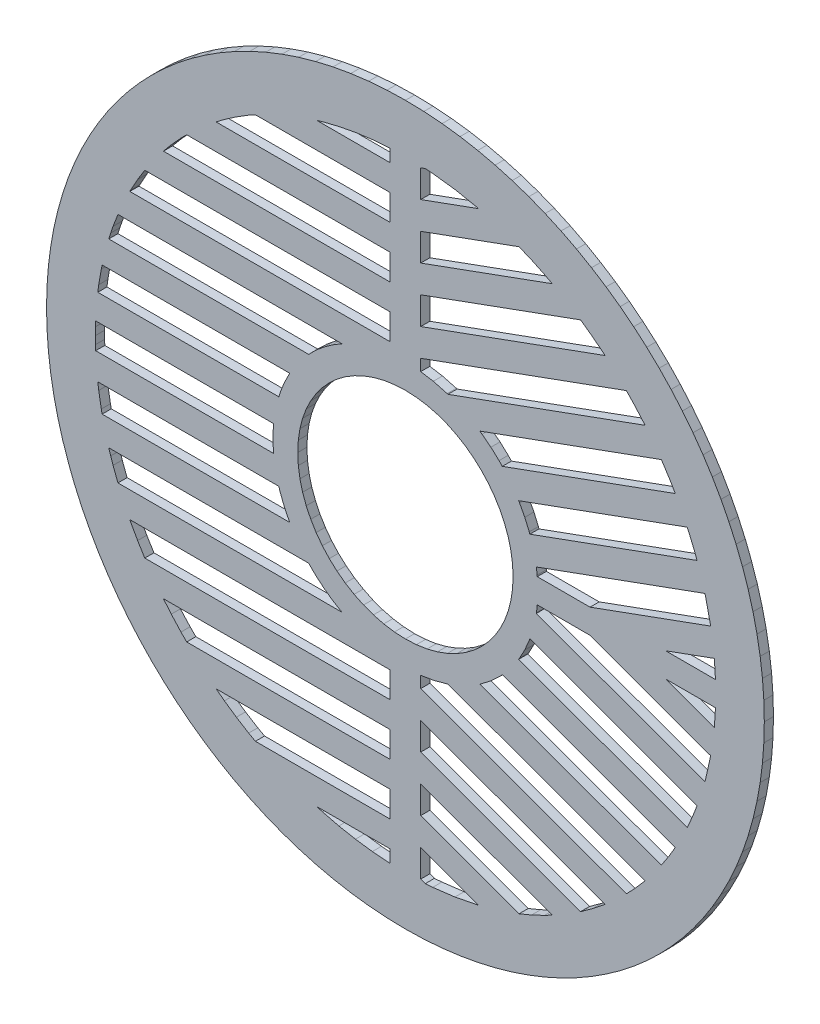
SolidWorks part; units mm, degrees
ref_plane "Front Plane" through (0, 0, 0) normal (0, 0, 1) x (1, 0, 0)
ref_plane "Top Plane" through (0, 0, 0) normal (0, 1, 0) x (1, 0, 0)
ref_plane "Right Plane" through (0, 0, 0) normal (1, 0, 0) x (0, 0, -1)
sketch "Model" plane through (0, 0, 0) normal (0, 0, 1) x (1, 0, 0)
  line L0 (88.7253, -26.6817) -> (90.6925, -27.2511)
  line L1 (90.6925, -27.2511) -> (96.018, -28.5686)
  line L2 (96.018, -28.5686) -> (101.4499, -29.6019)
  line L3 (101.4499, -29.6019) -> (106.9798, -30.3428)
  line L4 (106.9798, -30.3428) -> (112.5994, -30.7829)
  line L5 (112.5994, -30.7829) -> (113.8278, -30.8296)
  line L6 (113.8278, -30.8296) -> (113.8278, -26.6817)
  line L7 (113.8278, -26.6817) -> (88.7253, -26.6817)
  line L8 (121.8278, -20.8713) -> (121.8278, -29.8813)
  line L9 (121.8278, -29.8813) -> (124.32, -30.7884)
  line L10 (124.32, -30.7884) -> (126.7677, -30.6053)
  line L11 (126.7677, -30.6053) -> (134.0501, -29.7079)
  line L12 (134.0501, -29.7079) -> (141.1631, -28.3079)
  line L13 (141.1631, -28.3079) -> (141.8166, -28.1466)
  line L14 (141.8166, -28.1466) -> (121.8278, -20.8713)
  line L15 (55.7826, -9.7483) -> (58.5159, -11.8148)
  line L16 (58.5159, -11.8148) -> (62.4239, -14.4936)
  line L17 (62.4239, -14.4936) -> (66.4601, -16.992)
  line L18 (66.4601, -16.992) -> (68.6597, -18.215)
  line L19 (68.6597, -18.215) -> (113.8278, -18.215)
  line L20 (113.8278, -18.215) -> (113.8278, -9.7483)
  line L21 (113.8278, -9.7483) -> (55.7826, -9.7483)
  line L22 (121.8278, -2.8512) -> (121.8278, -11.8612)
  line L23 (121.8278, -11.8612) -> (155.0747, -23.9621)
  line L24 (155.0747, -23.9621) -> (159.1619, -22.2578)
  line L25 (159.1619, -22.2578) -> (163.4116, -20.2484)
  line L26 (163.4116, -20.2484) -> (165.9394, -18.9065)
  line L27 (165.9394, -18.9065) -> (121.8278, -2.8512)
  line L28 (38.529, 7.185) -> (41.103, 4.0802)
  line L29 (41.103, 4.0802) -> (44.2827, 0.587)
  line L30 (44.2827, 0.587) -> (46.1485, -1.2817)
  line L31 (46.1485, -1.2817) -> (113.8278, -1.2817)
  line L32 (113.8278, -1.2817) -> (113.8278, 7.185)
  line L33 (113.8278, 7.185) -> (38.529, 7.185)
  line L34 (121.8278, 15.1689) -> (121.8278, 6.1588)
  line L35 (121.8278, 6.1588) -> (175.2272, -13.2769)
  line L36 (175.2272, -13.2769) -> (175.4731, -13.1157)
  line L37 (175.4731, -13.1157) -> (179.2461, -10.3883)
  line L38 (179.2461, -10.3883) -> (182.8862, -7.495)
  line L39 (182.8862, -7.495) -> (183.2425, -7.1843)
  line L40 (183.2425, -7.1843) -> (121.8278, 15.1689)
  line L41 (27.5169, 24.1183) -> (27.767, 23.6121)
  line L42 (27.767, 23.6121) -> (30.0733, 19.4496)
  line L43 (30.0733, 19.4496) -> (32.4163, 15.6517)
  line L44 (32.4163, 15.6517) -> (113.8278, 15.6517)
  line L45 (113.8278, 15.6517) -> (113.8278, 24.1183)
  line L46 (113.8278, 24.1183) -> (27.5169, 24.1183)
  line L47 (131.7462, 29.579) -> (131.4924, 29.4887)
  line L48 (131.4924, 29.4887) -> (126.9693, 28.258)
  line L49 (126.9693, 28.258) -> (122.2643, 27.5174)
  line L50 (122.2643, 27.5174) -> (121.8278, 27.4842)
  line L51 (121.8278, 27.4842) -> (121.8278, 24.1789)
  line L52 (121.8278, 24.1789) -> (190.2361, -0.7197)
  line L53 (190.2361, -0.7197) -> (192.9542, 2.1249)
  line L54 (192.9542, 2.1249) -> (196.0078, 5.6266)
  line L55 (196.0078, 5.6266) -> (196.3549, 6.0633)
  line L56 (196.3549, 6.0633) -> (131.7462, 29.579)
  line L57 (20.6207, 41.0517) -> (21.2461, 39.06)
  line L58 (21.2461, 39.06) -> (22.0242, 36.7752)
  line L59 (22.0242, 36.7752) -> (23.6208, 32.585)
  line L60 (23.6208, 32.585) -> (97.0674, 32.585)
  line L61 (97.0674, 32.585) -> (96.343, 32.9771)
  line L62 (96.343, 32.9771) -> (93.8383, 34.5222)
  line L63 (93.8383, 34.5222) -> (91.4501, 36.2285)
  line L64 (91.4501, 36.2285) -> (89.1859, 38.0885)
  line L65 (89.1859, 38.0885) -> (87.0533, 40.0946)
  line L66 (87.0533, 40.0946) -> (86.1436, 41.0517)
  line L67 (86.1436, 41.0517) -> (20.6207, 41.0517)
  line L68 (149.5731, 41.1106) -> (148.5103, 40.0025)
  line L69 (148.5103, 40.0025) -> (145.8287, 37.5359)
  line L70 (145.8287, 37.5359) -> (142.9467, 35.2989)
  line L71 (142.9467, 35.2989) -> (142.1932, 34.7866)
  line L72 (142.1932, 34.7866) -> (201.689, 13.1319)
  line L73 (201.689, 13.1319) -> (204.1847, 16.94)
  line L74 (204.1847, 16.94) -> (206.2746, 20.4729)
  line L75 (206.2746, 20.4729) -> (149.5731, 41.1106)
  line L76 (158.6054, 55.8432) -> (158.401, 55.2685)
  line L77 (158.401, 55.2685) -> (156.9405, 51.8729)
  line L78 (156.9405, 51.8729) -> (155.2067, 48.6339)
  line L79 (155.2067, 48.6339) -> (154.9215, 48.174)
  line L80 (154.9215, 48.174) -> (210.1637, 28.0674)
  line L81 (210.1637, 28.0674) -> (210.7706, 29.3509)
  line L82 (210.7706, 29.3509) -> (212.5867, 33.7061)
  line L83 (212.5867, 33.7061) -> (213.385, 35.905)
  line L84 (213.385, 35.905) -> (158.6054, 55.8432)
  line L85 (17.0156, 57.985) -> (17.3272, 55.6856)
  line L86 (17.3272, 55.6856) -> (18.1668, 50.8298)
  line L87 (18.1668, 50.8298) -> (18.4432, 49.5183)
  line L88 (18.4432, 49.5183) -> (79.9425, 49.5183)
  line L89 (79.9425, 49.5183) -> (79.064, 51.1652)
  line L90 (79.064, 51.1652) -> (77.8204, 53.8559)
  line L91 (77.8204, 53.8559) -> (76.7588, 56.6421)
  line L92 (76.7588, 56.6421) -> (76.3343, 57.985)
  line L93 (76.3343, 57.985) -> (17.0156, 57.985)
  line L94 (203.0823, 66.685) -> (219.0323, 60.8797)
  line L95 (219.0323, 60.8797) -> (219.118, 61.7451)
  line L96 (219.118, 61.7451) -> (219.4279, 66.685)
  line L97 (219.4279, 66.685) -> (203.0823, 66.685)
  line L98 (161.0286, 66.685) -> (160.9954, 66.2485)
  line L99 (160.9954, 66.2485) -> (160.7598, 64.3465)
  line L100 (160.7598, 64.3465) -> (160.7157, 64.0851)
  line L101 (160.7157, 64.0851) -> (215.9618, 43.9772)
  line L102 (215.9618, 43.9772) -> (216.2455, 45.0195)
  line L103 (216.2455, 45.0195) -> (217.809, 52.0719)
  line L104 (217.809, 52.0719) -> (217.8484, 52.3006)
  line L105 (217.8484, 52.3006) -> (178.3275, 66.685)
  line L106 (178.3275, 66.685) -> (161.0286, 66.685)
  line L107 (16.3211, 74.9183) -> (16.2588, 73.2256)
  line L108 (16.2588, 73.2256) -> (16.2277, 70.685)
  line L109 (16.2277, 70.685) -> (16.2588, 68.1444)
  line L110 (16.2588, 68.1444) -> (16.3211, 66.4517)
  line L111 (16.3211, 66.4517) -> (74.6416, 66.4517)
  line L112 (74.6416, 66.4517) -> (74.6332, 66.5222)
  line L113 (74.6332, 66.5222) -> (74.4858, 68.5908)
  line L114 (74.4858, 68.5908) -> (74.4361, 70.685)
  line L115 (74.4361, 70.685) -> (74.4858, 72.7792)
  line L116 (74.4858, 72.7792) -> (74.6332, 74.8478)
  line L117 (74.6332, 74.8478) -> (74.6416, 74.9183)
  line L118 (74.6416, 74.9183) -> (16.3211, 74.9183)
  line L119 (219.0323, 80.4903) -> (203.0823, 74.685)
  line L120 (203.0823, 74.685) -> (219.4279, 74.685)
  line L121 (219.4279, 74.685) -> (219.118, 79.6249)
  line L122 (219.118, 79.6249) -> (219.0323, 80.4903)
  line L123 (18.4432, 91.8517) -> (18.1668, 90.5402)
  line L124 (18.1668, 90.5402) -> (17.3272, 85.6844)
  line L125 (17.3272, 85.6844) -> (17.0156, 83.385)
  line L126 (17.0156, 83.385) -> (76.3343, 83.385)
  line L127 (76.3343, 83.385) -> (76.7588, 84.7279)
  line L128 (76.7588, 84.7279) -> (77.8204, 87.5141)
  line L129 (77.8204, 87.5141) -> (79.064, 90.2048)
  line L130 (79.064, 90.2048) -> (79.9425, 91.8517)
  line L131 (79.9425, 91.8517) -> (18.4432, 91.8517)
  line L132 (215.9618, 97.3928) -> (160.7157, 77.2849)
  line L133 (160.7157, 77.2849) -> (160.7598, 77.0235)
  line L134 (160.7598, 77.0235) -> (160.9954, 75.1216)
  line L135 (160.9954, 75.1216) -> (161.0286, 74.685)
  line L136 (161.0286, 74.685) -> (178.3275, 74.685)
  line L137 (178.3275, 74.685) -> (217.8484, 89.0694)
  line L138 (217.8484, 89.0694) -> (217.809, 89.2981)
  line L139 (217.809, 89.2981) -> (216.2455, 96.3505)
  line L140 (216.2455, 96.3505) -> (215.9618, 97.3928)
  line L141 (117.8278, 105.9628) -> (114.2208, 105.7807)
  line L142 (114.2208, 105.7807) -> (110.7181, 105.2461)
  line L143 (110.7181, 105.2461) -> (107.3372, 104.3768)
  line L144 (107.3372, 104.3768) -> (104.0961, 103.1905)
  line L145 (104.0961, 103.1905) -> (101.0123, 101.705)
  line L146 (101.0123, 101.705) -> (98.1036, 99.9379)
  line L147 (98.1036, 99.9379) -> (95.3878, 97.9071)
  line L148 (95.3878, 97.9071) -> (92.8826, 95.6302)
  line L149 (92.8826, 95.6302) -> (90.6057, 93.1249)
  line L150 (90.6057, 93.1249) -> (88.5749, 90.4091)
  line L151 (88.5749, 90.4091) -> (86.8078, 87.5005)
  line L152 (86.8078, 87.5005) -> (85.3223, 84.4167)
  line L153 (85.3223, 84.4167) -> (84.136, 81.1755)
  line L154 (84.136, 81.1755) -> (83.2667, 77.7947)
  line L155 (83.2667, 77.7947) -> (82.7321, 74.292)
  line L156 (82.7321, 74.292) -> (82.55, 70.685)
  line L157 (82.55, 70.685) -> (82.7321, 67.0781)
  line L158 (82.7321, 67.0781) -> (83.2667, 63.5753)
  line L159 (83.2667, 63.5753) -> (84.136, 60.1945)
  line L160 (84.136, 60.1945) -> (85.3223, 56.9533)
  line L161 (85.3223, 56.9533) -> (86.8078, 53.8695)
  line L162 (86.8078, 53.8695) -> (88.5749, 50.9609)
  line L163 (88.5749, 50.9609) -> (90.6057, 48.2451)
  line L164 (90.6057, 48.2451) -> (92.8826, 45.7399)
  line L165 (92.8826, 45.7399) -> (95.3878, 43.463)
  line L166 (95.3878, 43.463) -> (98.1036, 41.4321)
  line L167 (98.1036, 41.4321) -> (101.0123, 39.6651)
  line L168 (101.0123, 39.6651) -> (104.0961, 38.1795)
  line L169 (104.0961, 38.1795) -> (107.3372, 36.9932)
  line L170 (107.3372, 36.9932) -> (110.7181, 36.1239)
  line L171 (110.7181, 36.1239) -> (114.2208, 35.5894)
  line L172 (114.2208, 35.5894) -> (117.8278, 35.4072)
  line L173 (117.8278, 35.4072) -> (121.4347, 35.5894)
  line L174 (121.4347, 35.5894) -> (124.9375, 36.1239)
  line L175 (124.9375, 36.1239) -> (128.3183, 36.9932)
  line L176 (128.3183, 36.9932) -> (131.5595, 38.1795)
  line L177 (131.5595, 38.1795) -> (134.6433, 39.6651)
  line L178 (134.6433, 39.6651) -> (137.5519, 41.4321)
  line L179 (137.5519, 41.4321) -> (140.2677, 43.463)
  line L180 (140.2677, 43.463) -> (142.7729, 45.7399)
  line L181 (142.7729, 45.7399) -> (145.0498, 48.2451)
  line L182 (145.0498, 48.2451) -> (147.0807, 50.9609)
  line L183 (147.0807, 50.9609) -> (148.8477, 53.8695)
  line L184 (148.8477, 53.8695) -> (150.3333, 56.9533)
  line L185 (150.3333, 56.9533) -> (151.5195, 60.1945)
  line L186 (151.5195, 60.1945) -> (152.3888, 63.5753)
  line L187 (152.3888, 63.5753) -> (152.9234, 67.0781)
  line L188 (152.9234, 67.0781) -> (153.1056, 70.685)
  line L189 (153.1056, 70.685) -> (152.9234, 74.292)
  line L190 (152.9234, 74.292) -> (152.3888, 77.7947)
  line L191 (152.3888, 77.7947) -> (151.5195, 81.1755)
  line L192 (151.5195, 81.1755) -> (150.3333, 84.4167)
  line L193 (150.3333, 84.4167) -> (148.8477, 87.5005)
  line L194 (148.8477, 87.5005) -> (147.0807, 90.4091)
  line L195 (147.0807, 90.4091) -> (145.0498, 93.1249)
  line L196 (145.0498, 93.1249) -> (142.7729, 95.6302)
  line L197 (142.7729, 95.6302) -> (140.2677, 97.9071)
  line L198 (140.2677, 97.9071) -> (137.5519, 99.9379)
  line L199 (137.5519, 99.9379) -> (134.6433, 101.705)
  line L200 (134.6433, 101.705) -> (131.5595, 103.1905)
  line L201 (131.5595, 103.1905) -> (128.3183, 104.3768)
  line L202 (128.3183, 104.3768) -> (124.9375, 105.2461)
  line L203 (124.9375, 105.2461) -> (121.4347, 105.7807)
  line L204 (121.4347, 105.7807) -> (117.8278, 105.9628)
  line L205 (23.6208, 108.785) -> (22.0242, 104.5948)
  line L206 (22.0242, 104.5948) -> (21.2461, 102.31)
  line L207 (21.2461, 102.31) -> (20.6207, 100.3183)
  line L208 (20.6207, 100.3183) -> (86.1436, 100.3183)
  line L209 (86.1436, 100.3183) -> (87.0533, 101.2754)
  line L210 (87.0533, 101.2754) -> (89.1859, 103.2815)
  line L211 (89.1859, 103.2815) -> (91.4501, 105.1415)
  line L212 (91.4501, 105.1415) -> (93.8383, 106.8478)
  line L213 (93.8383, 106.8478) -> (96.343, 108.3929)
  line L214 (96.343, 108.3929) -> (97.0674, 108.785)
  line L215 (97.0674, 108.785) -> (23.6208, 108.785)
  line L216 (210.1637, 113.3026) -> (154.9215, 93.196)
  line L217 (154.9215, 93.196) -> (155.2067, 92.7361)
  line L218 (155.2067, 92.7361) -> (156.9405, 89.4971)
  line L219 (156.9405, 89.4971) -> (158.401, 86.1015)
  line L220 (158.401, 86.1015) -> (158.6054, 85.5268)
  line L221 (158.6054, 85.5268) -> (213.385, 105.465)
  line L222 (213.385, 105.465) -> (212.5867, 107.6639)
  line L223 (212.5867, 107.6639) -> (210.7706, 112.0191)
  line L224 (210.7706, 112.0191) -> (210.1637, 113.3026)
  line L225 (32.4163, 125.7183) -> (30.0733, 121.9204)
  line L226 (30.0733, 121.9204) -> (27.767, 117.7579)
  line L227 (27.767, 117.7579) -> (27.5169, 117.2517)
  line L228 (27.5169, 117.2517) -> (113.8278, 117.2517)
  line L229 (113.8278, 117.2517) -> (113.8278, 125.7183)
  line L230 (113.8278, 125.7183) -> (32.4163, 125.7183)
  line L231 (201.689, 128.2381) -> (142.1932, 106.5834)
  line L232 (142.1932, 106.5834) -> (142.9467, 106.0711)
  line L233 (142.9467, 106.0711) -> (145.8287, 103.8342)
  line L234 (145.8287, 103.8342) -> (148.5103, 101.3675)
  line L235 (148.5103, 101.3675) -> (149.5731, 100.2594)
  line L236 (149.5731, 100.2594) -> (206.2746, 120.8971)
  line L237 (206.2746, 120.8971) -> (204.1847, 124.43)
  line L238 (204.1847, 124.43) -> (201.689, 128.2381)
  line L239 (190.2361, 142.0897) -> (121.8278, 117.1911)
  line L240 (121.8278, 117.1911) -> (121.8278, 113.8858)
  line L241 (121.8278, 113.8858) -> (122.2643, 113.8526)
  line L242 (122.2643, 113.8526) -> (126.9693, 113.112)
  line L243 (126.9693, 113.112) -> (131.4924, 111.8813)
  line L244 (131.4924, 111.8813) -> (131.7462, 111.791)
  line L245 (131.7462, 111.791) -> (196.3549, 135.3067)
  line L246 (196.3549, 135.3067) -> (196.0078, 135.7434)
  line L247 (196.0078, 135.7434) -> (192.9542, 139.2451)
  line L248 (192.9542, 139.2451) -> (190.2361, 142.0897)
  line L249 (46.1485, 142.6517) -> (44.2827, 140.783)
  line L250 (44.2827, 140.783) -> (41.103, 137.2898)
  line L251 (41.103, 137.2898) -> (38.529, 134.185)
  line L252 (38.529, 134.185) -> (113.8278, 134.185)
  line L253 (113.8278, 134.185) -> (113.8278, 142.6517)
  line L254 (113.8278, 142.6517) -> (46.1485, 142.6517)
  line L255 (175.2272, 154.647) -> (121.8278, 135.2112)
  line L256 (121.8278, 135.2112) -> (121.8278, 126.2011)
  line L257 (121.8278, 126.2011) -> (183.2425, 148.5543)
  line L258 (183.2425, 148.5543) -> (182.8862, 148.865)
  line L259 (182.8862, 148.865) -> (179.2461, 151.7583)
  line L260 (179.2461, 151.7583) -> (175.4731, 154.4858)
  line L261 (175.4731, 154.4858) -> (175.2272, 154.647)
  line L262 (68.6597, 159.585) -> (66.4601, 158.362)
  line L263 (66.4601, 158.362) -> (62.4239, 155.8636)
  line L264 (62.4239, 155.8636) -> (58.5159, 153.1848)
  line L265 (58.5159, 153.1848) -> (55.7826, 151.1183)
  line L266 (55.7826, 151.1183) -> (113.8278, 151.1183)
  line L267 (113.8278, 151.1183) -> (113.8278, 159.585)
  line L268 (113.8278, 159.585) -> (68.6597, 159.585)
  line L269 (155.0747, 165.3321) -> (121.8278, 153.2312)
  line L270 (121.8278, 153.2312) -> (121.8278, 144.2212)
  line L271 (121.8278, 144.2212) -> (165.9394, 160.2765)
  line L272 (165.9394, 160.2765) -> (163.4116, 161.6184)
  line L273 (163.4116, 161.6184) -> (159.1619, 163.6278)
  line L274 (159.1619, 163.6278) -> (155.0747, 165.3321)
  line L275 (124.32, 172.1584) -> (121.8278, 171.2513)
  line L276 (121.8278, 171.2513) -> (121.8278, 162.2413)
  line L277 (121.8278, 162.2413) -> (141.8166, 169.5166)
  line L278 (141.8166, 169.5166) -> (141.1631, 169.6779)
  line L279 (141.1631, 169.6779) -> (134.0501, 171.0779)
  line L280 (134.0501, 171.0779) -> (126.7677, 171.9753)
  line L281 (126.7677, 171.9753) -> (124.32, 172.1584)
  line L282 (113.8278, 172.1996) -> (112.5994, 172.1529)
  line L283 (112.5994, 172.1529) -> (106.9798, 171.7128)
  line L284 (106.9798, 171.7128) -> (101.4499, 170.9719)
  line L285 (101.4499, 170.9719) -> (96.018, 169.9386)
  line L286 (96.018, 169.9386) -> (90.6925, 168.6211)
  line L287 (90.6925, 168.6211) -> (88.7253, 168.0517)
  line L288 (88.7253, 168.0517) -> (113.8278, 168.0517)
  line L289 (113.8278, 168.0517) -> (113.8278, 172.1996)
  line L290 (117.8278, 188.2851) -> (123.8795, 188.1321)
  line L291 (123.8795, 188.1321) -> (129.8517, 187.6779)
  line L292 (129.8517, 187.6779) -> (135.7371, 186.9301)
  line L293 (135.7371, 186.9301) -> (141.5283, 185.8959)
  line L294 (141.5283, 185.8959) -> (147.2179, 184.5827)
  line L295 (147.2179, 184.5827) -> (152.7984, 182.998)
  line L296 (152.7984, 182.998) -> (158.2626, 181.1492)
  line L297 (158.2626, 181.1492) -> (163.603, 179.0435)
  line L298 (163.603, 179.0435) -> (168.8123, 176.6885)
  line L299 (168.8123, 176.6885) -> (173.883, 174.0914)
  line L300 (173.883, 174.0914) -> (178.8077, 171.2597)
  line L301 (178.8077, 171.2597) -> (183.5791, 168.2009)
  line L302 (183.5791, 168.2009) -> (188.1898, 164.9221)
  line L303 (188.1898, 164.9221) -> (192.6324, 161.431)
  line L304 (192.6324, 161.431) -> (196.8994, 157.7347)
  line L305 (196.8994, 157.7347) -> (200.9836, 153.8408)
  line L306 (200.9836, 153.8408) -> (204.8775, 149.7567)
  line L307 (204.8775, 149.7567) -> (208.5737, 145.4896)
  line L308 (208.5737, 145.4896) -> (212.0649, 141.047)
  line L309 (212.0649, 141.047) -> (215.3436, 136.4363)
  line L310 (215.3436, 136.4363) -> (218.4025, 131.6649)
  line L311 (218.4025, 131.6649) -> (221.2342, 126.7402)
  line L312 (221.2342, 126.7402) -> (223.8312, 121.6695)
  line L313 (223.8312, 121.6695) -> (226.1863, 116.4603)
  line L314 (226.1863, 116.4603) -> (228.2919, 111.1199)
  line L315 (228.2919, 111.1199) -> (230.1408, 105.6557)
  line L316 (230.1408, 105.6557) -> (231.7255, 100.0751)
  line L317 (231.7255, 100.0751) -> (233.0387, 94.3855)
  line L318 (233.0387, 94.3855) -> (234.0729, 88.5943)
  line L319 (234.0729, 88.5943) -> (234.8207, 82.7089)
  line L320 (234.8207, 82.7089) -> (235.2749, 76.7367)
  line L321 (235.2749, 76.7367) -> (235.4279, 70.685)
  line L322 (235.4279, 70.685) -> (235.2749, 64.6333)
  line L323 (235.2749, 64.6333) -> (234.8207, 58.6611)
  line L324 (234.8207, 58.6611) -> (234.0729, 52.7757)
  line L325 (234.0729, 52.7757) -> (233.0387, 46.9845)
  line L326 (233.0387, 46.9845) -> (231.7255, 41.2949)
  line L327 (231.7255, 41.2949) -> (230.1408, 35.7143)
  line L328 (230.1408, 35.7143) -> (228.2919, 30.2502)
  line L329 (228.2919, 30.2502) -> (226.1863, 24.9097)
  line L330 (226.1863, 24.9097) -> (223.8312, 19.7005)
  line L331 (223.8312, 19.7005) -> (221.2342, 14.6298)
  line L332 (221.2342, 14.6298) -> (218.4025, 9.7051)
  line L333 (218.4025, 9.7051) -> (215.3436, 4.9337)
  line L334 (215.3436, 4.9337) -> (212.0649, 0.323)
  line L335 (212.0649, 0.323) -> (208.5737, -4.1196)
  line L336 (208.5737, -4.1196) -> (204.8775, -8.3866)
  line L337 (204.8775, -8.3866) -> (200.9836, -12.4708)
  line L338 (200.9836, -12.4708) -> (196.8994, -16.3647)
  line L339 (196.8994, -16.3647) -> (192.6324, -20.0609)
  line L340 (192.6324, -20.0609) -> (188.1898, -23.5521)
  line L341 (188.1898, -23.5521) -> (183.5791, -26.8308)
  line L342 (183.5791, -26.8308) -> (178.8077, -29.8897)
  line L343 (178.8077, -29.8897) -> (173.883, -32.7214)
  line L344 (173.883, -32.7214) -> (168.8123, -35.3185)
  line L345 (168.8123, -35.3185) -> (163.603, -37.6735)
  line L346 (163.603, -37.6735) -> (158.2626, -39.7792)
  line L347 (158.2626, -39.7792) -> (152.7984, -41.628)
  line L348 (152.7984, -41.628) -> (147.2179, -43.2127)
  line L349 (147.2179, -43.2127) -> (141.5283, -44.5259)
  line L350 (141.5283, -44.5259) -> (135.7371, -45.5601)
  line L351 (135.7371, -45.5601) -> (129.8517, -46.3079)
  line L352 (129.8517, -46.3079) -> (123.8795, -46.7621)
  line L353 (123.8795, -46.7621) -> (117.8278, -46.9151)
  line L354 (117.8278, -46.9151) -> (111.7761, -46.7621)
  line L355 (111.7761, -46.7621) -> (105.8038, -46.3079)
  line L356 (105.8038, -46.3079) -> (99.9184, -45.5601)
  line L357 (99.9184, -45.5601) -> (94.1273, -44.5259)
  line L358 (94.1273, -44.5259) -> (88.4377, -43.2127)
  line L359 (88.4377, -43.2127) -> (82.8571, -41.628)
  line L360 (82.8571, -41.628) -> (77.3929, -39.7792)
  line L361 (77.3929, -39.7792) -> (72.0525, -37.6735)
  line L362 (72.0525, -37.6735) -> (66.8433, -35.3185)
  line L363 (66.8433, -35.3185) -> (61.7726, -32.7214)
  line L364 (61.7726, -32.7214) -> (56.8478, -29.8897)
  line L365 (56.8478, -29.8897) -> (52.0764, -26.8308)
  line L366 (52.0764, -26.8308) -> (47.4658, -23.5521)
  line L367 (47.4658, -23.5521) -> (43.0232, -20.0609)
  line L368 (43.0232, -20.0609) -> (38.7561, -16.3647)
  line L369 (38.7561, -16.3647) -> (34.6719, -12.4708)
  line L370 (34.6719, -12.4708) -> (30.7781, -8.3866)
  line L371 (30.7781, -8.3866) -> (27.0818, -4.1196)
  line L372 (27.0818, -4.1196) -> (23.5907, 0.323)
  line L373 (23.5907, 0.323) -> (20.3119, 4.9337)
  line L374 (20.3119, 4.9337) -> (17.253, 9.7051)
  line L375 (17.253, 9.7051) -> (14.4214, 14.6298)
  line L376 (14.4214, 14.6298) -> (11.8243, 19.7005)
  line L377 (11.8243, 19.7005) -> (9.4693, 24.9097)
  line L378 (9.4693, 24.9097) -> (7.3636, 30.2502)
  line L379 (7.3636, 30.2502) -> (5.5147, 35.7143)
  line L380 (5.5147, 35.7143) -> (3.93, 41.2949)
  line L381 (3.93, 41.2949) -> (2.6169, 46.9845)
  line L382 (2.6169, 46.9845) -> (1.5827, 52.7757)
  line L383 (1.5827, 52.7757) -> (0.8348, 58.6611)
  line L384 (0.8348, 58.6611) -> (0.3807, 64.6333)
  line L385 (0.3807, 64.6333) -> (0.2277, 70.685)
  line L386 (0.2277, 70.685) -> (0.3807, 76.7367)
  line L387 (0.3807, 76.7367) -> (0.8348, 82.7089)
  line L388 (0.8348, 82.7089) -> (1.5827, 88.5943)
  line L389 (1.5827, 88.5943) -> (2.6169, 94.3855)
  line L390 (2.6169, 94.3855) -> (3.93, 100.0751)
  line L391 (3.93, 100.0751) -> (5.5147, 105.6557)
  line L392 (5.5147, 105.6557) -> (7.3636, 111.1199)
  line L393 (7.3636, 111.1199) -> (9.4693, 116.4603)
  line L394 (9.4693, 116.4603) -> (11.8243, 121.6695)
  line L395 (11.8243, 121.6695) -> (14.4214, 126.7402)
  line L396 (14.4214, 126.7402) -> (17.253, 131.6649)
  line L397 (17.253, 131.6649) -> (20.3119, 136.4363)
  line L398 (20.3119, 136.4363) -> (23.5907, 141.047)
  line L399 (23.5907, 141.047) -> (27.0818, 145.4896)
  line L400 (27.0818, 145.4896) -> (30.7781, 149.7567)
  line L401 (30.7781, 149.7567) -> (34.6719, 153.8408)
  line L402 (34.6719, 153.8408) -> (38.7561, 157.7347)
  line L403 (38.7561, 157.7347) -> (43.0232, 161.431)
  line L404 (43.0232, 161.431) -> (47.4658, 164.9221)
  line L405 (47.4658, 164.9221) -> (52.0764, 168.2009)
  line L406 (52.0764, 168.2009) -> (56.8478, 171.2597)
  line L407 (56.8478, 171.2597) -> (61.7726, 174.0914)
  line L408 (61.7726, 174.0914) -> (66.8433, 176.6885)
  line L409 (66.8433, 176.6885) -> (72.0525, 179.0435)
  line L410 (72.0525, 179.0435) -> (77.3929, 181.1492)
  line L411 (77.3929, 181.1492) -> (82.8571, 182.998)
  line L412 (82.8571, 182.998) -> (88.4377, 184.5827)
  line L413 (88.4377, 184.5827) -> (94.1273, 185.8959)
  line L414 (94.1273, 185.8959) -> (99.9184, 186.9301)
  line L415 (99.9184, 186.9301) -> (105.8038, 187.6779)
  line L416 (105.8038, 187.6779) -> (111.7761, 188.1321)
  line L417 (111.7761, 188.1321) -> (117.8278, 188.2851)
extrude "Boss-Extrude1" add sketch "Model" along normal blind 3
sketch "Sketch2" plane through (0, 0, 3) normal (0, 0, 1) x (1, 0, 0)
  line L0 (113.8278, 138.4183) -> (121.8278, 133.1698) construction
  line L1 (113.8278, 134.185) -> (113.8278, 142.6517) construction
  line L2 (121.8278, 135.2112) -> (121.8278, 126.2011) construction
  line L3 (65.236, 74.9183) -> (55.4242, 66.4517) construction
  line L4 (74.6416, 74.9183) -> (16.3211, 74.9183) construction
  line L5 (16.3211, 66.4517) -> (74.6416, 66.4517) construction
  line L6 (60.3301, 70.685) -> (176.3269, 70.685) construction
  line L7 (117.8278, 135.7941) -> (117.8278, 52.8894) construction
  line L8 (112.8278, 35.4072) -> (122.8278, 35.4072)
  line L9 (112.8278, 105.9628) -> (122.8278, 105.9628)
  line L10 (112.8278, 105.9628) -> (112.8278, 185.3508)
  line L11 (112.8278, 185.3508) -> (122.8278, 185.3508)
  line L12 (122.8278, 105.9628) -> (122.8278, 185.3508)
  line L13 (112.8278, 105.9628) -> (122.8278, 185.3508) construction
  line L14 (112.8278, 185.3508) -> (122.8278, 105.9628) construction
  line L15 (122.8278, 35.4072) -> (122.8278, -43.9808)
  line L16 (112.8278, 35.4072) -> (112.8278, -43.9808)
  line L17 (112.8278, -43.9808) -> (122.8278, -43.9808)
  point P16 (117.8278, 70.685)
  point P17 (117.8278, 145.6568)
  dimension "D1" = 10
extrude "Boss-Extrude2" add sketch "Sketch2" against normal up to surface (3 mm away) up to face at (130.2533, 169.6998, 0)
